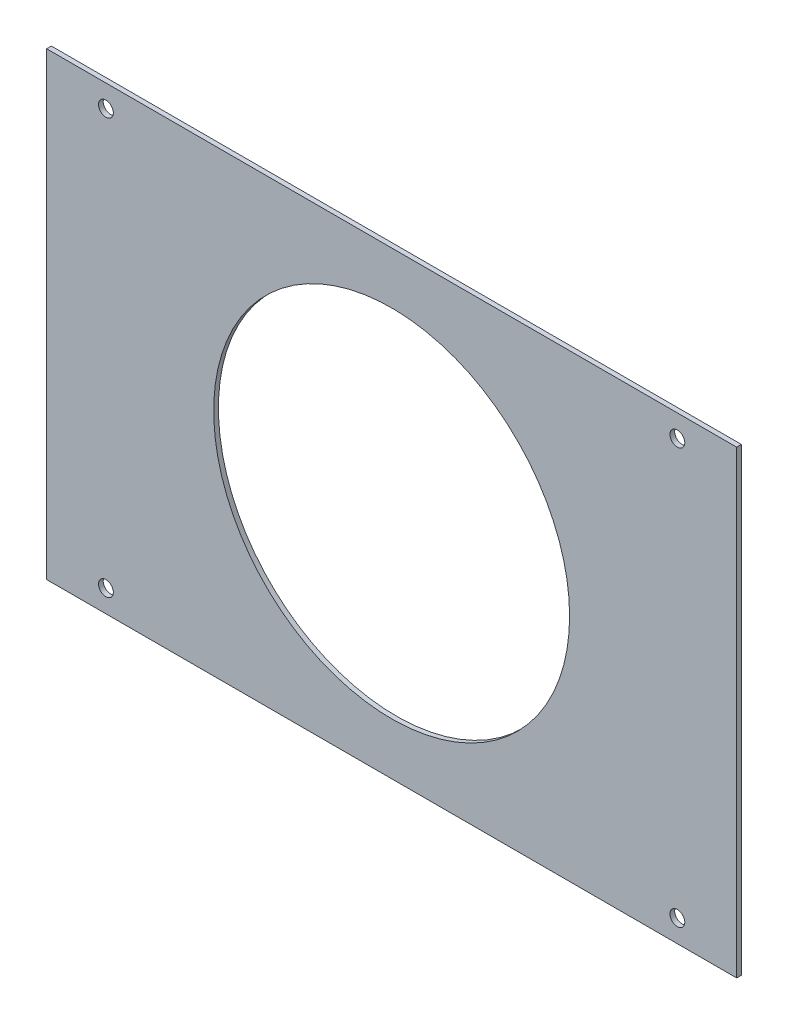
SolidWorks part; units mm, degrees
material "6061 Alloy"
ref_plane "Front Plane" through (0, 0, 0) normal (0, 0, 1) x (1, 0, 0)
ref_plane "Top Plane" through (0, 0, 0) normal (0, 1, 0) x (1, 0, 0)
ref_plane "Right Plane" through (0, 0, 0) normal (1, 0, 0) x (0, 0, -1)
sketch "Sketch1" plane through (0, 0, 0) normal (0, 0, 1) x (1, 0, 0)
  line L0 (-82.7574, 17.7712) -> (-82.7574, -137.2288)
  line L3 (-82.7574, 17.7712) -> (149.9102, 17.7712)
  line L4 (149.9102, 17.7712) -> (149.9102, -137.2288)
  line L5 (149.9102, -137.2288) -> (-82.7574, -137.2288)
  dimension "D1" = 155
  dimension "D2" = 232.6677
extrude "Boss-Extrude1" add sketch "Sketch1" along normal blind 1.5875 contours L3 L4 L5 L0
sketch "Sketch2" plane through (0, 0, 1.5875) normal (0, 0, 1) x (1, 0, 0)
  circle A0 centre (33.5764, -59.7288) radius 60
extrude "Cut-Extrude1" cut sketch "Sketch2" against normal through all
sketch "Sketch6" plane through (0, 0, 1.5875) normal (0, 0, 1) x (1, 0, 0)
  line L0 (-82.7574, 17.7712) -> (-82.7574, -137.2288) construction
  line L1 (-82.7574, 17.7712) -> (149.9102, 17.7712) construction
  line L2 (149.9102, 17.7712) -> (149.9102, -137.2288) construction
  line L4 (149.9102, -137.2288) -> (-82.7574, -137.2288) construction
  circle A1 centre (-62.7574, 10.2712) radius 2.5
  circle A2 centre (129.9102, 10.2712) radius 2.5
  circle A3 centre (-62.7574, -129.7288) radius 2.5
  circle A4 centre (129.9102, -129.7288) radius 2.5
  dimension "D1" = 20
  dimension "D3" = 7.5
  dimension "D5" = 20
  dimension "D2" = 7.5
  dimension "D4" = 20
  dimension "D6" = 7.5
extrude "Cut-Extrude2" cut sketch "Sketch6" against normal through all contours A2 | A4 | A1 | A3
sketch "Sketch7" plane through (0, 0, 0) normal (0, 0, -1) x (-1, 0, 0)
  line L0 (-33.5764, 0.2712) -> (-33.5764, 17.7712)
  line L8 (82.7574, -137.2288) -> (82.7574, 17.7712)
  line L9 (82.7574, 17.7712) -> (-149.9102, 17.7712)
  line L10 (-149.9102, 17.7712) -> (-149.9102, -137.2288)
  line L11 (-149.9102, -137.2288) -> (82.7574, -137.2288)
  circle A1 centre (-33.5764, -59.7288) radius 60
